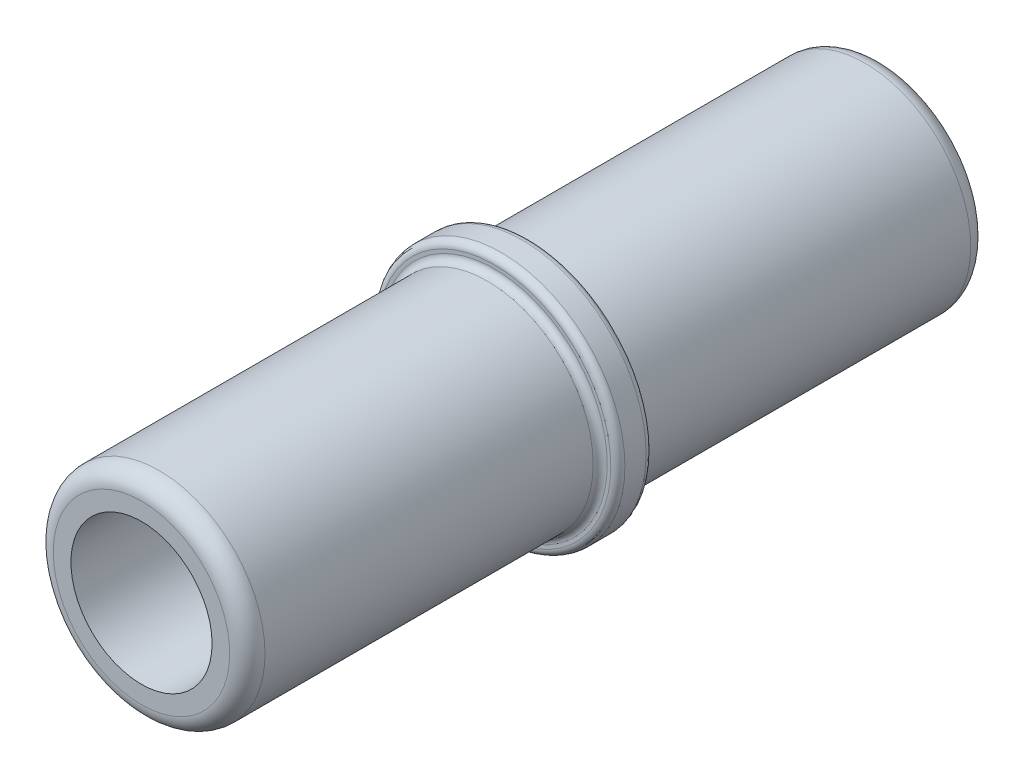
SolidWorks part; units mm, degrees
ref_plane "Front Plane" through (0, 0, 0) normal (0, 0, 1) x (1, 0, 0)
ref_plane "Top Plane" through (0, 0, 0) normal (0, 1, 0) x (1, 0, 0)
ref_plane "Right Plane" through (0, 0, 0) normal (1, 0, 0) x (0, 0, -1)
sketch "Sketch1" plane through (0, 0, 0) normal (0, 0, 1) x (1, 0, 0)
  circle A0 centre (0, 0) radius 0.35
  dimension "D1" = 0.7
extrude "Boss-Extrude2" add sketch "Sketch1" along normal blind 0.1 contours A0
sketch "Sketch4" plane through (0, 0, 0.1) normal (0, 0, 1) x (1, 0, 0)
  circle A0 centre (0, 0) radius 0.3
extrude "Boss-Extrude3" add sketch "Sketch4" along normal blind 1
sketch "Sketch5" plane through (0, 0, 0) normal (0, 0, -1) x (-1, 0, 0)
  circle A0 centre (0, 0) radius 0.3
extrude "Boss-Extrude4" add sketch "Sketch5" along normal blind 1
fillet "Fillet1" radius 0.05 1 edges at (0.3, 0, 1.1)
fillet "Fillet2" radius 0.05 1 edges at (-0.3, 0, -1)
fillet "Fillet3" radius 0.02 1 edges at (0.35, 0, 0.1)
fillet "Fillet4" radius 0.02 1 edges at (0.3, 0, 0)
fillet "Fillet5" radius 0.02 1 edges at (0.35, 0, 0)
fillet "Fillet6" radius 0.02 1 edges at (0.3, 0, 0.1)
sketch "Sketch6" plane through (0, 0, 1.1) normal (0, 0, 1) x (1, 0, 0)
  circle A0 centre (0, 0) radius 0.2
extrude "Cut-Extrude1" cut sketch "Sketch6" against normal blind 2.1
